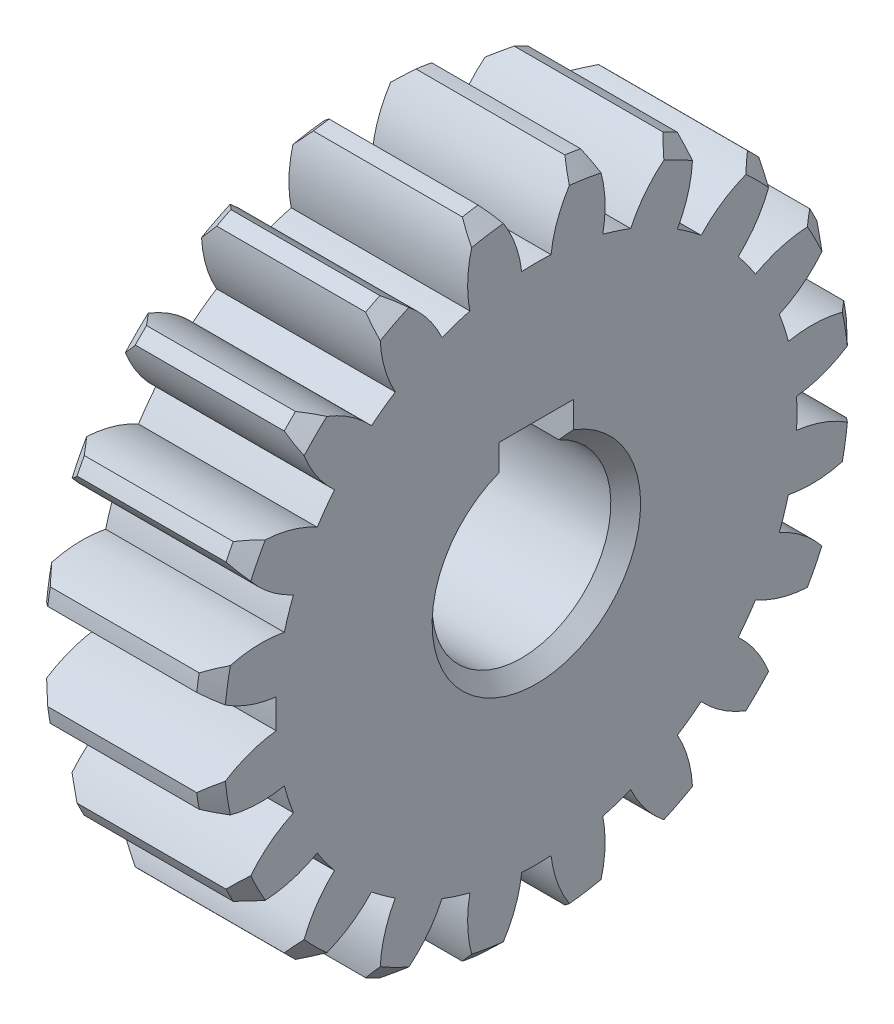
SolidWorks part; units mm, degrees
ref_plane "Plane1" through (0, 0, 0) normal (0, 0, 1) x (1, 0, 0)
ref_plane "Plane2" through (0, 0, 0) normal (0, 1, 0) x (1, 0, 0)
ref_plane "Plane3" through (0, 0, 0) normal (1, 0, 0) x (0, 0, -1)
sketch "HoldingSke" plane through (0, 0, 0) normal (0, 1, 0) x (1, 0, 0)
  line L0 (0, 0) -> (0.4698, -0.171)
  line L1 (-15, 0) -> (100, 0) construction
  line L2 (0, 0) -> (-2.1039, 2.3779)
  line L3 (0, 0) -> (-11.863, 4.5341)
  line L4 (0, 0) -> (8.1152, 2.9537)
  line L5 (0, 0) -> (-46.8476, -17.4728)
  line L6 (0, 0) -> (-9.9476, -6.7116)
  line L7 (-2.1039, 2.3779) -> (8.6586, 51.2059)
  line L8 (-76.2, 54.61) -> (-73.9, 54.61)
  line L9 (-71.009, 38.7566) -> (-53.1078, 45.2721)
  line L10 (-76.2, 71.12) -> (104.1128, 71.12)
  line L11 (0, 0) -> (-12, 0)
  line L12 (-76.2, 101.6) -> (-76.133, 101.6)
  line L13 (24.9733, 27.94) -> (52.9518, 28.4284)
  line L14 (24.9733, 27.94) -> (24.9743, 27.94)
  line L15 (24.9733, 27.94) -> (100.4006, 29.5858)
  line L16 (-63.627, -2) -> (-12.827, -2)
  circle A0 centre (0, 0) radius 6
  circle A1 centre (0, 0) radius 17.499
  circle A2 centre (0, 0) radius 37.5
  circle A3 centre (0, 0) radius 6
  dimension "MHD" = 34.998
  dimension "Hub_dia" = 75
  dimension "Bore" = 12
  dimension "MBD" = 12
  dimension "Num_teeth" = 20
  dimension "Pitch" = 0.5
  dimension "Overall_len" = 50
  dimension "Show_teeth" = 20
  dimension "Thickness" = 12
  dimension "OAL" = 50.0001
  dimension "T_dim" = 2.3
  dimension "Ap" = 20
  dimension "H" = 19.05
  dimension "Pitch_radius" = 180.3128
  dimension "Width" = 12
  dimension "Backlash" = 0.067
  dimension "Addendum_fac" = 1
  dimension "Dedendum_fac" = 1.25
  dimension "Clearance_fac" = 0.25
  dimension "Dedendum_add" = 0.001
  dimension "Module" = 2
sketch "BasProSke" plane through (0, 0, 0) normal (0, 1, 0) x (1, 0, 0)
  line L0 (-10, 0) -> (60, 0) construction
  line L1 (0, 0) -> (0, 22)
  line L2 (0, 0) -> (12, 0)
  line L3 (12, 0) -> (12, 22)
  line L4 (12, 22) -> (0, 22)
  dimension "Thickness" = 12
  dimension "Diameter" = 44
revolve "Base-Revolve" add sketch "BasProSke" angle 360 about L0
sketch "TooCutSke" plane through (0, 0, 0) normal (1, 0, 0) x (0, 0, -1)
  line L1 (0, 0) -> (0, 107) construction
  line L2 (0, 0) -> (-1.6864, 19.9288) construction
  line L3 (0, 0) -> (-6.2409, 39.4033) construction
  line L4 (-1.6864, 19.9288) -> (-3.1204, 19.7016) construction
  arc A0 (0.9862, 17.4712) -> (-0.9862, 17.4712) centre (0, 0) ccw
  arc A1 (2.9329, 21.8293) -> (-2.9329, 21.8293) centre (0, 0) ccw
  circle A2 centre (0, 0) radius 20 construction
  circle A3 centre (0, 0) radius 18.7939 construction
  arc A4 (-0.9862, 17.4712) -> (-2.9329, 21.8293) centre (-8.9313, 16.536) ccw
  arc A5 (2.9329, 21.8293) -> (0.9862, 17.4712) centre (8.9313, 16.536) ccw
  dimension "Root_dia" = 34.998
  dimension "Overcut_dia" = 44.0508
  dimension "Pitch_dia" = 40
  dimension "Base_dia" = 37.5877
  dimension "Flank_rad" = 8
  dimension "Half_ang" = 9
  dimension "Half_CT" = 1.4519
extrude "ToothCut" cut sketch "TooCutSke" along normal through all
fillet "Breaks" [suppressed] radius 0.04
fillet "RootFillets" [suppressed] radius 0.501
pattern_circular "TeethCuts" count 20 every 18 about axis through (-10, 0, 0) along (1, 0, 0) of "ToothCut", "RootFillets", "Breaks"
sketch "HubNeaOneSke" plane through (0, 0, 0) normal (-1, 0, 0) x (0, 0, 1)
  circle A0 centre (0, 0) radius 17.499
  dimension "Diameter" = 34.998
extrude "HubNearOne" [suppressed] add sketch "HubNeaOneSke" along normal blind 38.0001
sketch "HubNeaBotSke" plane through (0, 0, 0) normal (-1, 0, 0) x (0, 0, 1)
  circle A0 centre (0, 0) radius 17.499
  dimension "Diameter" = 34.998
extrude "HubNearBoth" [suppressed] add sketch "HubNeaBotSke" along normal blind 19
ref_plane "FarPln" through (12, 0, 0) normal (1, 0, 0) x (0, 0, -1)
sketch "HubFarSke" plane through (12, 0, 0) normal (1, 0, 0) x (0, 0, -1)
  circle A0 centre (0, 0) radius 17.499
  dimension "Diameter" = 34.998
extrude "HubFar" [suppressed] add sketch "HubFarSke" along normal blind 19
sketch "BorSke" plane through (0, 0, 0) normal (1, 0, 0) x (0, 0, -1)
  circle A0 centre (0, 0) radius 6
  dimension "Diameter" = 12
extrude "Bore" cut sketch "BorSke" along normal mid plane 100.0001
sketch "KeySke" plane through (0, 0, 0) normal (1, 0, 0) x (0, 0, -1)
  line L0 (-2.5, 0) -> (-2.5, 8.3)
  line L1 (-2.5, 8.3) -> (2.5, 8.3)
  line L2 (2.5, 8.3) -> (2.5, 0)
  line L3 (0, 0) -> (0, 34) construction
  line L4 (-2.5, 0) -> (2.5, 0)
  dimension "Offset" = 8.3
  dimension "Width" = 5
extrude "Keyway" cut sketch "KeySke" along normal mid plane 100.0001
pattern_circular "Keyway2" [suppressed] count 2 every 90 about axis through (-10, 0, 0) along (1, 0, 0)
chamfer "Chamfer1" distance 1 angle 45 42 edges at (12, -15.5563, 15.5563) (12, 15.5563, -15.5563) (12, 19.6021, -9.9878) (12, 21.7291, -3.4416) (12, -19.6021, 9.9878) (12, -21.7291, 3.4416) (12, -21.7291, -3.4416) (12, -19.6021, -9.9878) (12, -15.5563, -15.5563) (12, -9.9878, -19.6021) (12, -3.4416, -21.7291) (12, 3.4416, -21.7291) (12, 9.9878, -19.6021) (12, 21.7291, 3.4416) (12, 19.6021, 9.9878) (12, 15.5563, 15.5563) (12, -9.9878, 19.6021) (12, -3.4416, 21.7291) (12, 3.4416, 21.7291) (12, 9.9878, 19.6021) (0, -19.6021, 9.9878) (0, -21.7291, 3.4416) (0, -21.7291, -3.4416) (0, -19.6021, -9.9878) (0, -15.5563, -15.5563) (0, -9.9878, -19.6021) (0, -3.4416, -21.7291) (0, 3.4416, -21.7291) (0, 9.9878, -19.6021) (0, 15.5563, -15.5563) (0, 19.6021, -9.9878) (0, -15.5563, 15.5563) (0, -9.9878, 19.6021) (0, -3.4416, 21.7291) (0, 3.4416, 21.7291) (0, 9.9878, 19.6021) (0, 15.5563, 15.5563) (0, 19.6021, 9.9878) (0, 21.7291, 3.4416) (0, 21.7291, -3.4416) (0, -6, 0) (12, -6, 0)
equation "' \"Module@HoldingSke\" = 6.35"
equation "' \"Num_teeth@HoldingSke\" = 12"
equation "' \"Ap@HoldingSke\" =  20"
equation "' \"Ap@HoldingSke\" = 20"
equation "' \"Width@HoldingSke\" = 0.5 * 25.4"
equation "' \"Hub_dia@HoldingSke\"= 1 * 25.4"
equation "' \"Hub_dia@HoldingSke\" = 1 * 25.4"
equation "' \"Overall_len@HoldingSke\" = 1.0 * 25.4"
equation "' \"Bore@HoldingSke\" = 0.75 * 25.4"
equation "' \"T_dim@HoldingSke\" = 0.1 * 25.4"
equation "' \"Width@KeySke\" = 0.25 * 25.4"
equation "' \"Show_teeth@HoldingSke\" = 13"
equation "' \"Backlash@HoldingSke\" = 0.009 * 25.4"
equation "' \"Addendum_fac@HoldingSke\" = 1.0"
equation "' \"Dedendum_fac@HoldingSke\" = 1.25"
equation "' \"Dedendum_add@HoldingSke\" = 0.00005 * 25.4"
equation "' \"Clearance_fac@HoldingSke\" = 0.25"
equation "\"Pitch@HoldingSke\" = 1 / \"Module@HoldingSke\""
equation "\"Overcut_dia@TooCutSke\" = (\"Num_teeth@HoldingSke\" + 2 * \"Addendum_fac@HoldingSke\") / \"Pitch@HoldingSke\" + 0.002 * 25.4"
equation "\"Pitch_dia@TooCutSke\" = \"Num_teeth@HoldingSke\" / \"Pitch@HoldingSke\""
equation "\"Base_dia@TooCutSke\" = \"Num_teeth@HoldingSke\" / \"Pitch@HoldingSke\" * cos((\"Ap@HoldingSke\"  * 3.14159265 / 180))"
equation "\"Root_dia@TooCutSke\" = (\"Num_teeth@HoldingSke\" + 2) / \"Pitch@HoldingSke\" - 2 * (\"Addendum_fac@HoldingSke\" + \"Dedendum_fac@HoldingSke\") / \"Pitch@HoldingSke\" - \"Dedendum_add@HoldingSke\" * 2"
equation "\"Half_ang@TooCutSke\" = 180 / \"Num_teeth@HoldingSke\""
equation "\"Half_CT@TooCutSke\" = \"Num_teeth@HoldingSke\" / \"Pitch@HoldingSke\" * sin((3.14159265 / 2 / \"Num_teeth@HoldingSke\")) / 2 - 7 * \"Backlash@HoldingSke\" / 4"
equation "\"Flank_rad@TooCutSke\" = \"Num_teeth@HoldingSke\" / \"Pitch@HoldingSke\" / 5"
equation "\"Radius@RootFillets\" = \"Clearance_fac@HoldingSke\" / \"Pitch@HoldingSke\" + \"Dedendum_add@HoldingSke\""
equation "\"Break_rad@Breaks\" = 0.02 / \"Pitch@HoldingSke\""
equation "\"Thickness@HoldingSke\" = \"Width@HoldingSke\""
equation "\"OAL@HoldingSke\" = \"Thickness@HoldingSke\""
equation "\"MHD@HoldingSke\" = (\"Num_teeth@HoldingSke\" + 2) / \"Pitch@HoldingSke\" - 2 * (\"Addendum_fac@HoldingSke\" + \"Dedendum_fac@HoldingSke\")  / \"Pitch@HoldingSke\" - \"Dedendum_add@HoldingSke\" * 2"
equation "\"MBD@HoldingSke\" = (\"Num_teeth@HoldingSke\" + 2) / \"Pitch@HoldingSke\" - 2 * (\"Addendum_fac@HoldingSke\" + \"Dedendum_fac@HoldingSke\")  / \"Pitch@HoldingSke\" - \"Dedendum_add@HoldingSke\" * 2 - 0.002 * 25.4"
equation "\"MHD@HoldingSke\" = ((sgn( \"MHD@HoldingSke\" - \"Hub_dia@HoldingSke\" )-1)*( \"MHD@HoldingSke\" - \"Hub_dia@HoldingSke\" ))/-2+ \"Hub_dia@HoldingSke\""
equation "\"MBD@HoldingSke\" = ((sgn( \"MBD@HoldingSke\" - \"Bore@HoldingSke\" )-1)*( \"MBD@HoldingSke\" - \"Bore@HoldingSke\" ))/-2+ \"Bore@HoldingSke\""
equation "\"OAL@HoldingSke\" = ((sgn( \"OAL@HoldingSke\" - \"Overall_len@HoldingSke\" )+1)*( \"OAL@HoldingSke\" - \"Overall_len@HoldingSke\" ))/2 + \"Overall_len@HoldingSke\" + 0.000002 * 25.4"
equation "\"Num_teeth@TeethCuts\" = int( \"Show_teeth@HoldingSke\" ) + 1"
equation "\"Num_teeth@TeethCuts\" = ((sgn( \"Num_teeth@TeethCuts\" - \"Num_teeth@HoldingSke\" )-1)*( \"Num_teeth@TeethCuts\" - \"Num_teeth@HoldingSke\" ))/-2+ \"Num_teeth@HoldingSke\""
equation "\"Num_teeth@TeethCuts\" = ((sgn( \"Num_teeth@TeethCuts\" - 2.0)+1)*( \"Num_teeth@TeethCuts\" - 2.0))/2 +2.0"
equation "\"Angle@TeethCuts\" = 360.0 / \"Num_teeth@HoldingSke\""
equation "\"Diameter@BasProSke\" = (\"Num_teeth@HoldingSke\" + 2 * \"Addendum_fac@HoldingSke\") / \"Pitch@HoldingSke\""
equation "\"Thickness@BasProSke\"  = \"Thickness@HoldingSke\""
equation "' \"Fillet_rad@BasProSke\" =  \"Thickness@HoldingSke\" * 0.05"
equation "' \"Fillet_rad@BasProSke\" = \"Thickness@HoldingSke\" * 0.05"
equation "\"MHD@HoldingSke\" = ((sgn( \"MHD@HoldingSke\" - \"Root_dia@TooCutSke\" )-1)*( \"MHD@HoldingSke\" - \"Root_dia@TooCutSke\" ))/-2+ \"Root_dia@TooCutSke\""
equation "\"Diameter@HubNeaOneSke\" = \"MHD@HoldingSke\""
equation "\"Length@HubNearOne\" = \"OAL@HoldingSke\" - \"Thickness@BasProSke\""
equation "\"Diameter@HubNeaBotSke\" = \"MHD@HoldingSke\""
equation "\"Length@HubNearBoth\" = ( \"OAL@HoldingSke\" - \"Thickness@BasProSke\" ) / 2.0"
equation "\"Thickness@FarPln\" = \"Thickness@BasProSke\""
equation "\"Diameter@HubFarSke\" = \"MHD@HoldingSke\""
equation "\"Length@HubFar\" = ( \"OAL@HoldingSke\" - \"Thickness@BasProSke\" ) / 2.0"
equation "\"Diameter@BorSke\" = \"MBD@HoldingSke\""
equation "\"D1@Bore\" = \"OAL@HoldingSke\" * 2.0"
equation "\"D1@Keyway\" = \"OAL@HoldingSke\" * 2.0"
equation "\"Offset@KeySke\" = \"T_dim@HoldingSke\" + \"MBD@HoldingSke\" / 2.0"
